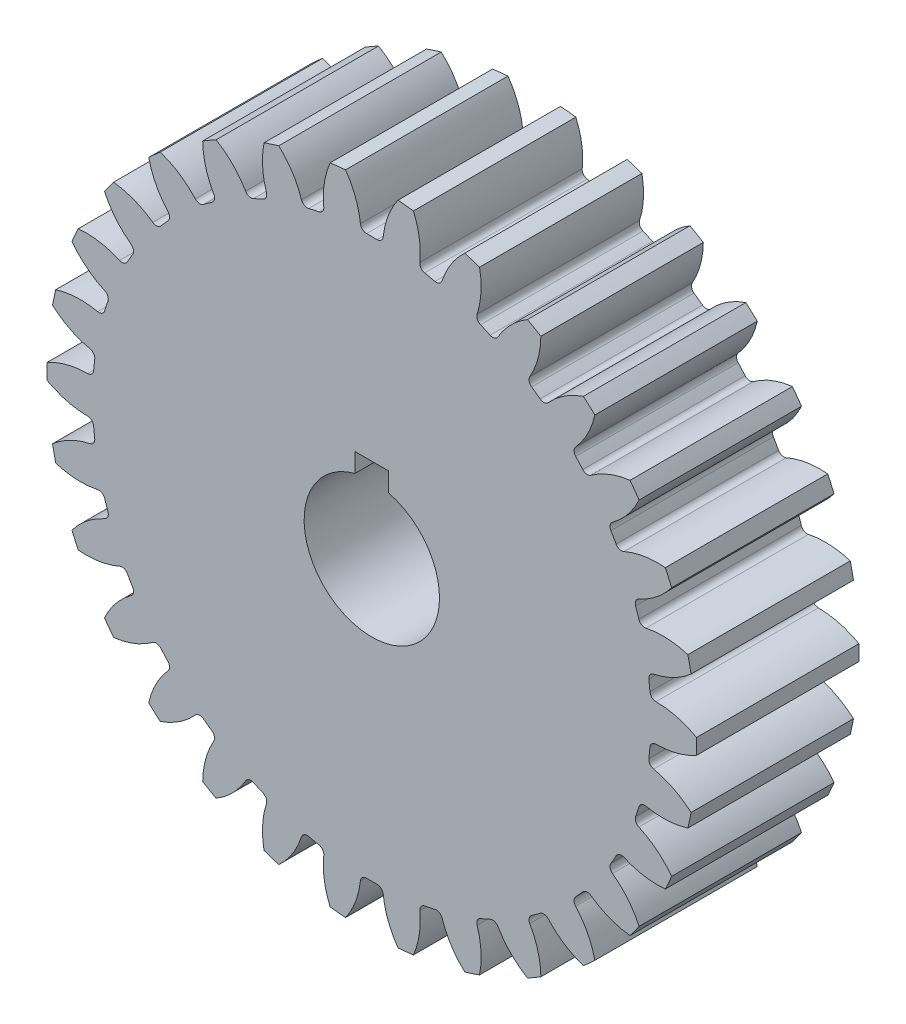
SolidWorks part; units mm, degrees
ref_plane "Ön Düzlem" through (0, 0, 0) normal (0, 0, 1) x (1, 0, 0)
ref_plane "Üst Düzlem" through (0, 0, 0) normal (0, 1, 0) x (1, 0, 0)
ref_plane "Sağ Düzlem" through (0, 0, 0) normal (1, 0, 0) x (0, 0, -1)
sketch "Sketch1" plane through (0, 0, 0) normal (0, 0, 1) x (1, 0, 0)
  circle A0 centre (0, 0) radius 45 construction
  circle A1 centre (0, 0) radius 48
  circle A2 centre (0, 0) radius 41.25
  dimension "D1" = 90
  dimension "D2" = 96
  dimension "D3" = 82.5
extrude "dişli kalınlığı" add sketch "Sketch1" along normal mid plane 24 contours A1 A2 | A2
sketch "Sketch2" plane through (0, 0, 0) normal (0, 0, 1) x (1, 0, 0)
  line L0 (0, 0) -> (0, -48) construction
  line L1 (2.3551, -44.9383) -> (-2.3551, -44.9383) construction
  line L2 (0, -38.4677) -> (3.7803, -48.854) construction
  line L3 (0, 0) -> (1.6234, -41.218) construction
  line L4 (0, 0) -> (-5.0174, -47.7371) construction
  line L5 (-2.3551, -44.9383) -> (-7.0396, -44.446) construction
  circle A0 centre (0, 0) radius 48 construction
  arc A1 (4.6148, -48.7822) -> (1.6234, -41.218) centre (13.9056, -40.7343) cw
  arc A2 (-4.6148, -48.7822) -> (-1.6234, -41.218) centre (-13.9056, -40.7343) ccw
  circle A3 centre (0, 0) radius 41.25 construction
  arc A4 (-1.6234, -41.218) -> (1.6234, -41.218) centre (0, 0) ccw
  circle A6 centre (0, 0) radius 45 construction
  circle A7 centre (0, 0) radius 49
  arc A8 (-4.6148, -48.7822) -> (4.6148, -48.7822) centre (0, 0) ccw
  point P20 (-4.6973, -44.6922)
  dimension "D2" = 6
  dimension "D3" = 20
  dimension "D1" = 1
extrude "Cut-Extrude1" cut sketch "Sketch2" against normal mid plane 24
fillet "Fillet1" radius 0.9 2 edges at (-1.6234, -41.218, 0) (1.6234, -41.218, 0)
pattern_circular "CirPattern1" count 30 over 360 about axis through (0, 0, 0) along (0, 0, 1) of "Cut-Extrude1", "Fillet1"
sketch "Sketch3" plane through (0, 0, 12) normal (0, 0, 1) x (1, 0, 0)
  line L1 (-2.5, 12.5) -> (2.5, 12.5)
  line L2 (-2.5, 12.5) -> (-2.5, 9.6825)
  line L4 (2.5, 12.5) -> (2.5, 9.6825)
  arc A0 (-2.5, 9.6825) -> (2.5, 9.6825) centre (0, 0) ccw
  point P3 (0, 10)
  dimension "D1" = 20
  dimension "D2" = 5
  dimension "D3" = 12.5
extrude "Cut-Extrude2" cut sketch "Sketch3" against normal blind 24
equation "\"m\"= 3mm'modül"
equation "\"n\"= 30'diş sayısı"
equation "\"D1@Sketch1\"=\"n\"*\"m\""
equation "\"D2@Sketch1\"=\"m\"*(\"n\"+2)"
equation "\"D3@Sketch1\"=\"m\"*(\"n\"-2.5)"
equation "\"D1@dişli kalınlığı\" = \"m\" * 8"
equation "\"D1@Fillet1\"=\"m\"*0.3"
equation "\"D1@Cut-Extrude1\"=\"m\"*8"
equation "\"D1@CirPattern1\"=\"n\""
equation "\"D2@Sketch2\"=180/\"n\""
equation "\"D1@Cut-Extrude2\"=\"m\"*8"
